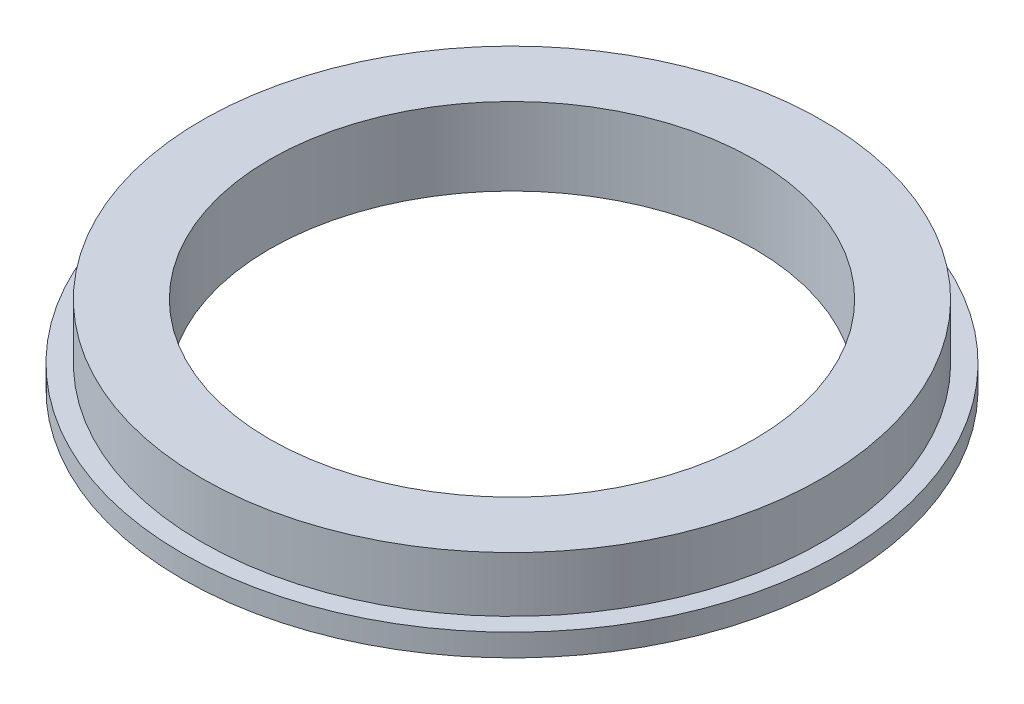
SolidWorks part; units mm, degrees
ref_plane "前视基准面" through (0, 0, 0) normal (0, 0, 1) x (1, 0, 0)
ref_plane "上视基准面" through (0, 0, 0) normal (0, 1, 0) x (1, 0, 0)
ref_plane "右视基准面" through (0, 0, 0) normal (1, 0, 0) x (0, 0, -1)
sketch "草图1" plane through (0, 0, 0) normal (0, 1, 0) x (1, 0, 0)
  circle A0 centre (0, 0) radius 16
  circle A1 centre (0, 0) radius 12.5
  dimension "D1" = 32
  dimension "D2" = 25
extrude "凸台-拉伸1" add sketch "草图1" along normal blind 2.85
sketch "草图2" plane through (0, 0, 0) normal (0, -1, 0) x (1, 0, 0)
  circle A0 centre (0, 0) radius 17
  circle A1 centre (0, 0) radius 12.5 construction
  circle A2 centre (0, 0) radius 12.5
  dimension "D1" = 34
extrude "凸台-拉伸2" add sketch "草图2" along normal blind 1.15
